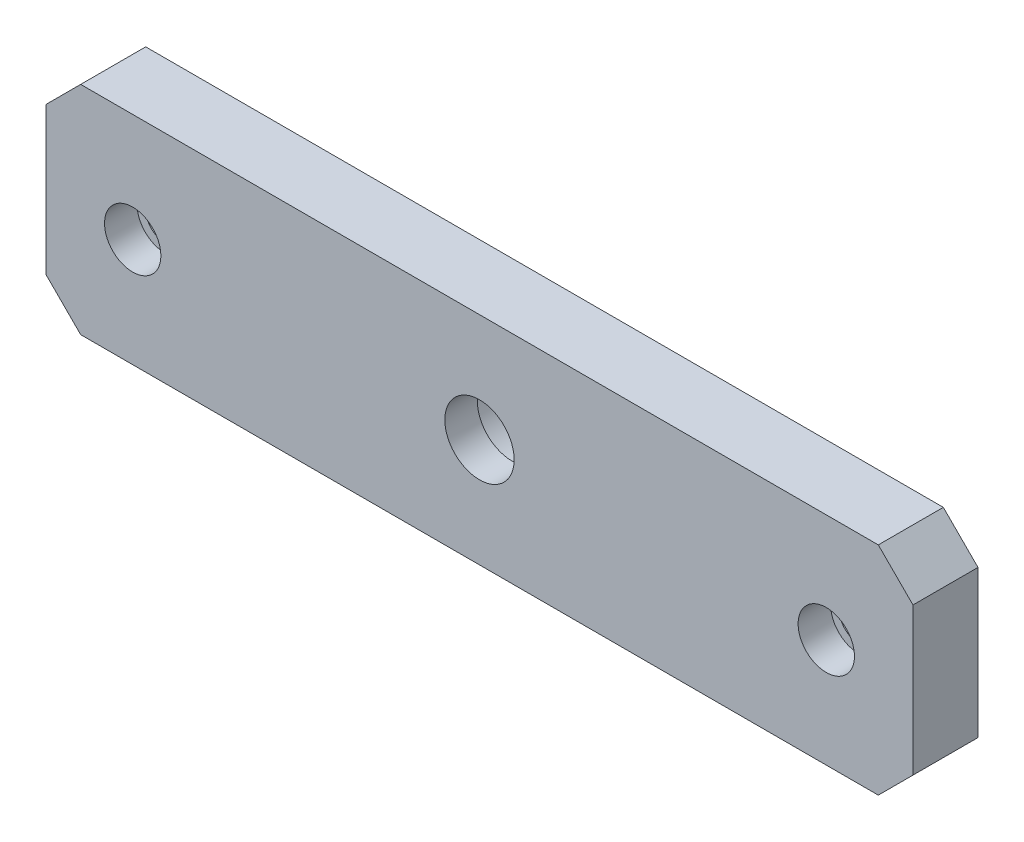
SolidWorks part; units mm, degrees
other "细节项目9"
ref_plane "前视基准面" through (0, 0, 0) normal (0, 0, 1) x (1, 0, 0)
ref_plane "上视基准面" through (0, 0, 0) normal (0, 1, 0) x (1, 0, 0)
ref_plane "右视基准面" through (0, 0, 0) normal (1, 0, 0) x (0, 0, -1)
sketch "草图1" plane through (0, 0, 0) normal (0, 0, 1) x (1, 0, 0)
  line L1 (0, 0) -> (200, 0)
  line L2 (0, 0) -> (0, 50)
  line L3 (0, 50) -> (200, 50)
  line L4 (200, 0) -> (200, 50)
  dimension "D1" = 200
  dimension "D2" = 50
extrude "凸台-拉伸1" add sketch "草图1" along normal blind 15
sketch "草图2" plane through (0, 0, 15) normal (0, 0, 1) x (1, 0, 0)
  line L0 (200, 0) -> (200, 50) construction
  line L1 (0, 0) -> (200, 0) construction
  circle A0 centre (20, 25) radius 4.5
  circle A1 centre (100, 25) radius 8
  circle A2 centre (180, 25) radius 4.5
  dimension "D1" = 9
  dimension "D2" = 9
  dimension "D3" = 16
  dimension "D4" = 80
  dimension "D5" = 80
  dimension "D6" = 20
  dimension "D7" = 25
  dimension "D8" = 25
  dimension "D9" = 25
extrude "切除-拉伸1" cut sketch "草图2" against normal through all
sketch "草图5" plane through (0, 0, 15) normal (0, 0, 1) x (1, 0, 0)
  circle A0 centre (20, 25) radius 6.5
  circle A1 centre (180, 25) radius 6.5
  dimension "D1" = 13
  dimension "D2" = 13
extrude "切除-拉伸4" cut sketch "草图5" against normal blind 7.5
sketch "草图6" plane through (0, 0, 0) normal (0, 0, -1) x (-1, 0, 0)
  circle A0 centre (-100, 25) radius 12
  dimension "D1" = 24
extrude "切除-拉伸5" cut sketch "草图6" against normal blind 7.5
chamfer "倒角1" distance 8 angle 45 4 edges at (0, 50, 7.5) (0, 0, 7.5) (200, 50, 7.5) (200, 0, 7.5)
